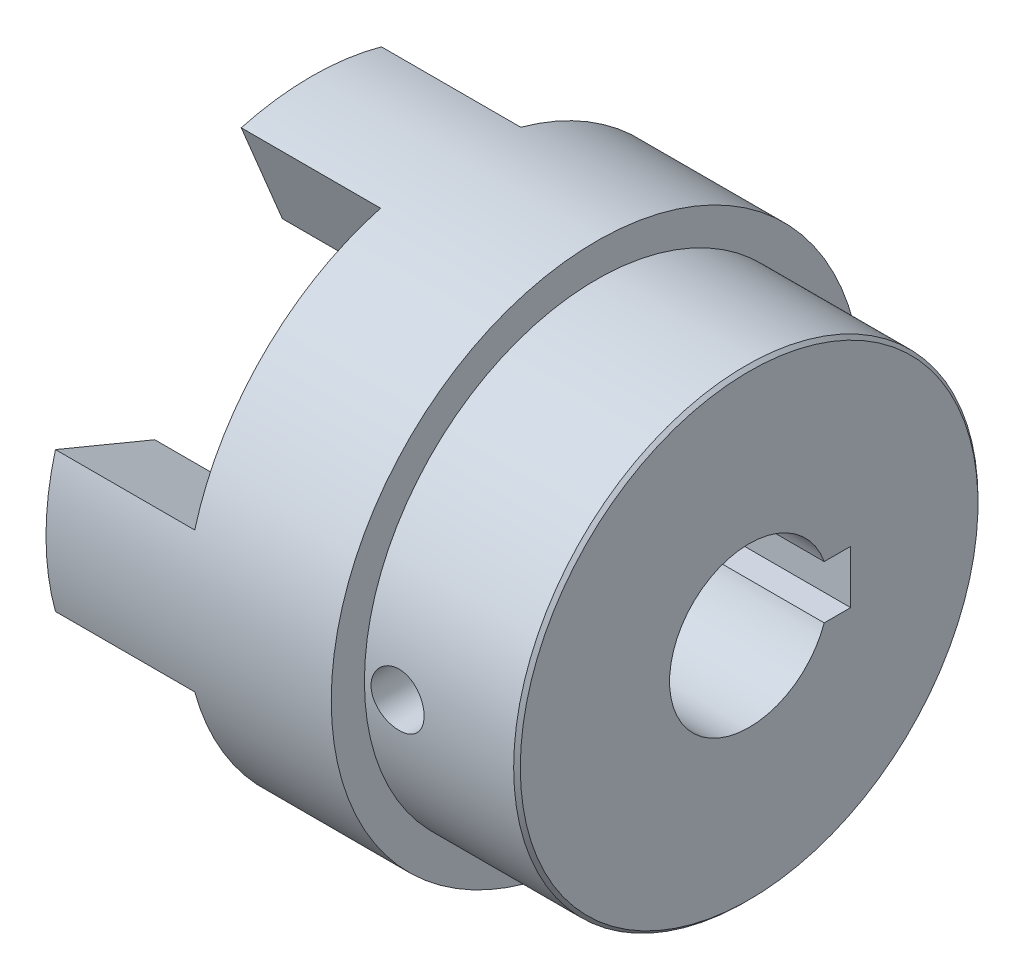
SolidWorks part; units mm, degrees
ref_plane "Front Plane" through (0, 0, 0) normal (0, 0, 1) x (1, 0, 0)
ref_plane "Top Plane" through (0, 0, 0) normal (0, 1, 0) x (1, 0, 0)
ref_plane "Right Plane" through (0, 0, 0) normal (1, 0, 0) x (0, 0, -1)
sketch "Sketch1" plane through (0, 0, 0) normal (0, 0, 1) x (1, 0, 0)
  line L0 (-50.16, 0) -> (50.16, 0) construction
  line L1 (-43, 40) -> (0, 40)
  line L2 (0, 40) -> (0, 35)
  line L3 (0, 35) -> (23, 35)
  line L4 (23, 35) -> (23, 0)
  line L5 (-43, 40) -> (-43, 0)
  line L6 (23, 0) -> (-43, 0)
  point P4 (0, 0)
  dimension "D1" = 43
  dimension "D2" = 66
  dimension "D3" = 80
  dimension "D4" = 70
revolve "Revolve1" add sketch "Sketch1" angle 360 about L0
chamfer "Chamfer1" distance 0.5 angle 45 1 edges at (23, 0, 35)
sketch "Sketch2" plane through (-43, 0, 0) normal (-1, 0, 0) x (0, 0, 1)
  line L0 (38.5783, -10.5694) -> (23.5997, -4.365)
  line L1 (0, 45.854) -> (0, 24) construction
  line L2 (-10.5694, 38.5783) -> (-4.365, 23.5997)
  line L3 (10.5694, 38.5783) -> (4.365, 23.5997)
  line L10 (38.5783, 10.5694) -> (23.5997, 4.365)
  line L11 (-10.5694, -38.5783) -> (-4.365, -23.5997)
  line L12 (10.5694, -38.5783) -> (4.365, -23.5997)
  line L13 (-38.5783, 10.5694) -> (-23.5997, 4.365)
  line L14 (-38.5783, -10.5694) -> (-23.5997, -4.365)
  arc A6 (4.365, 23.5997) -> (-4.365, 23.5997) centre (0, 0) ccw
  circle A9 centre (0, 0) radius 40 construction
  arc A10 (10.5694, 38.5783) -> (-10.5694, 38.5783) centre (0, 0) ccw
  arc A11 (23.5997, -4.365) -> (23.5997, 4.365) centre (0, 0) ccw
  arc A12 (38.5783, -10.5694) -> (38.5783, 10.5694) centre (0, 0) ccw
  arc A13 (-4.365, -23.5997) -> (4.365, -23.5997) centre (0, 0) ccw
  arc A14 (-10.5694, -38.5783) -> (10.5694, -38.5783) centre (0, 0) ccw
  arc A15 (-23.5997, 4.365) -> (-23.5997, -4.365) centre (0, 0) ccw
  arc A16 (-38.5783, 10.5694) -> (-38.5783, -10.5694) centre (0, 0) ccw
  circle M7 centre (0, 0) radius 40
  dimension "D1" = 8.73
  dimension "D2" = 22.5
  dimension "D3" = 24
  dimension "D4" = 4
extrude "Cut-Extrude1" cut sketch "Sketch2" against normal blind 21 flip side to cut contours L1 A6 L3 M7 | L1 A10 L2 A6 | A15 L13 L14 M7 | A11 L0 L10 M7 | A13 L11 L12 M7
sketch "Sketch4" plane through (0, 0, 0) normal (-1, 0, 0) x (0, 0, 1)
  line L0 (-50.8274, 0) -> (50.8274, 0) construction
  line L1 (-15.3, -4) -> (-11.3137, -4)
  line L2 (-15.3, 4) -> (-11.3137, 4)
  line L3 (-15.3, 4) -> (-15.3, -4)
  line L4 (-50.8274, 4) -> (50.8274, 4) construction
  line L5 (-50.8274, -4) -> (50.8274, -4) construction
  arc A0 (-11.3137, -4) -> (-11.3137, 4) centre (0, 0) ccw
  point P5 (0, 0)
  dimension "D1" = 24
  dimension "D4" = 15.3
  dimension "D2" = 4
  dimension "D3" = 4
extrude "Cut-Extrude2" cut sketch "Sketch4" against normal through all both and the other way through all
sketch "Sketch6" plane through (0, 0, 0) normal (0, 1, 0) x (1, 0, 0)
  line L0 (23, -34.5) -> (23, 34.5) construction
  circle A0 centre (5, 0) radius 4
  dimension "D1" = 8
  dimension "D2" = 18
extrude "Cut-Extrude3" cut sketch "Sketch6" against normal through all
pattern_circular "CirPattern1" count 2 every 90 of "Cut-Extrude3"
